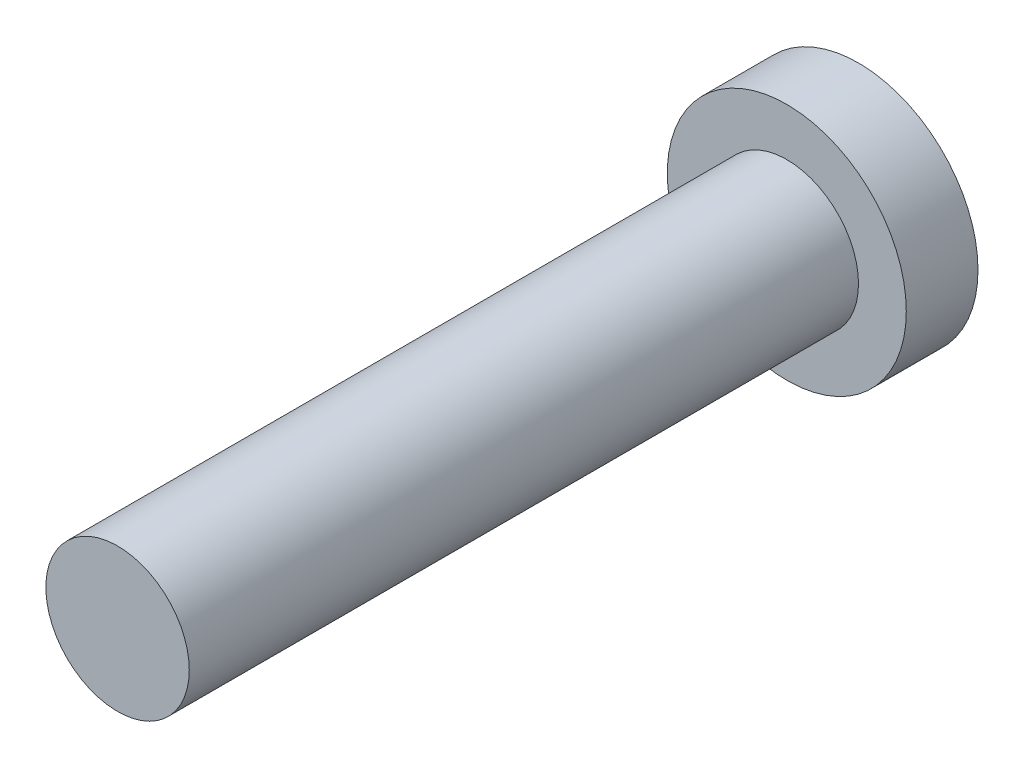
SolidWorks part; units mm, degrees
material "Alloy Steel"
ref_plane "Front Plane" through (0, 0, 0) normal (0, 0, 1) x (1, 0, 0)
ref_plane "Top Plane" through (0, 0, 0) normal (0, 1, 0) x (1, 0, 0)
ref_plane "Right Plane" through (0, 0, 0) normal (1, 0, 0) x (0, 0, -1)
sketch "Sketch1" plane through (0, 0, 0) normal (0, 0, 1) x (1, 0, 0)
  circle A0 centre (0, 0) radius 2.5
  dimension "D1" = 5
extrude "Boss-Extrude2" add sketch "Sketch1" along normal blind 1.5
sketch "Sketch4" plane through (0, 0, 1.5) normal (0, 0, 1) x (1, 0, 0)
  circle A0 centre (0, 0) radius 1.5
  dimension "D1" = 3
extrude "Boss-Extrude3" add sketch "Sketch4" along normal blind 14
